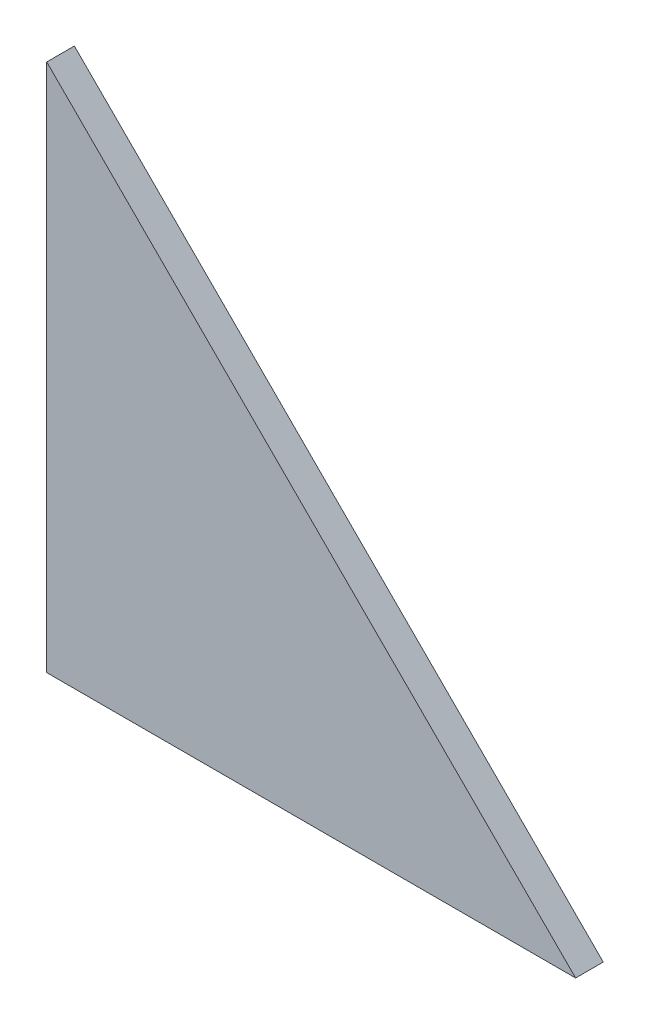
SolidWorks part; units mm, degrees
ref_plane "Plan de face" through (0, 0, 0) normal (0, 0, 1) x (1, 0, 0)
ref_plane "Plan de dessus" through (0, 0, 0) normal (0, 1, 0) x (1, 0, 0)
ref_plane "Plan de droite" through (0, 0, 0) normal (1, 0, 0) x (0, 0, -1)
sketch "Esquisse1" plane through (0, 0, 0) normal (0, 0, 1) x (1, 0, 0)
  line L0 (0, 0) -> (0, 383)
  line L1 (0, 383) -> (383, 0)
  line L2 (383, 0) -> (0, 0)
  dimension "D1" = 383
extrude "Boss.-Extru.1" add sketch "Esquisse1" along normal blind 20
